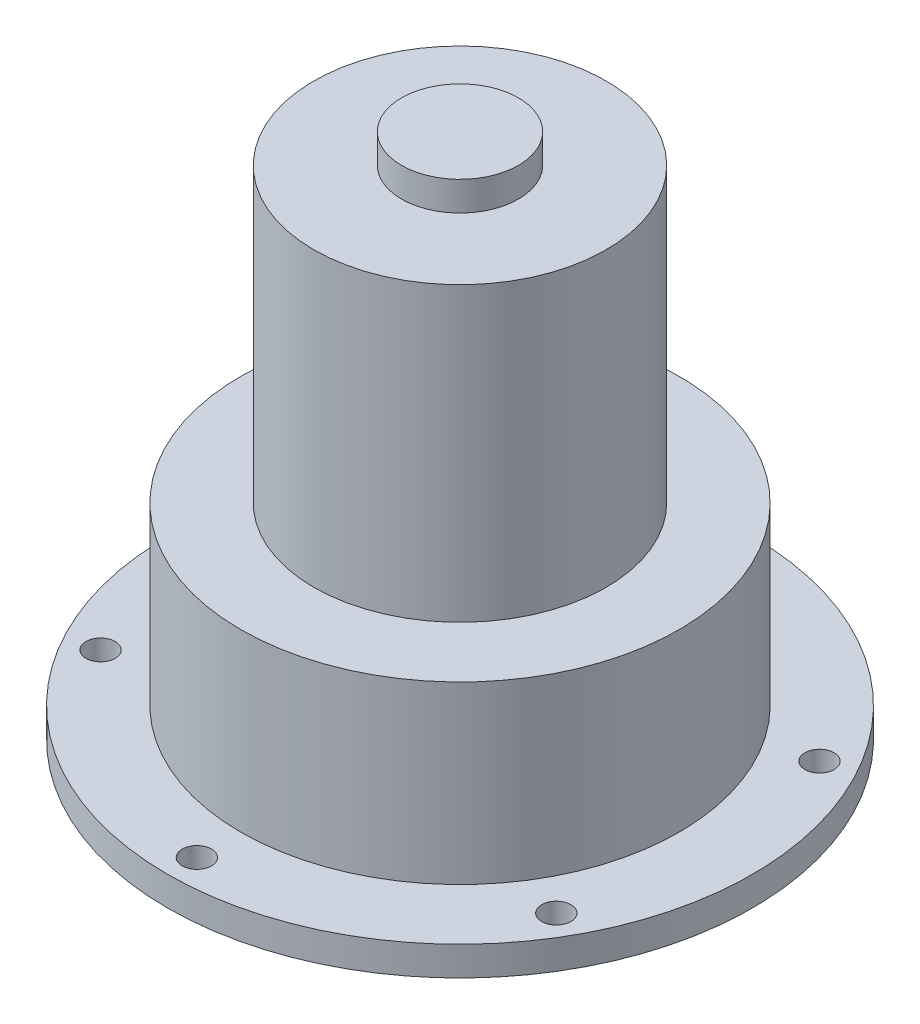
SolidWorks part; units mm, degrees
ref_plane "Front Plane" through (0, 0, 0) normal (0, 0, 1) x (1, 0, 0)
ref_plane "Top Plane" through (0, 0, 0) normal (0, 1, 0) x (1, 0, 0)
ref_plane "Right Plane" through (0, 0, 0) normal (1, 0, 0) x (0, 0, -1)
sketch "Sketch1" plane through (0, 0, 0) normal (0, 1, 0) x (1, 0, 0)
  circle A0 centre (0, 0) radius 37.5
  dimension "D1" = 75
extrude "Boss-Extrude1" add sketch "Sketch1" along normal blind 30
sketch "Sketch2" plane through (0, 30, 0) normal (0, 1, 0) x (1, 0, 0)
  circle A0 centre (0, 0) radius 25
  dimension "D1" = 50
extrude "Boss-Extrude2" add sketch "Sketch2" along normal blind 50
sketch "Sketch3" plane through (0, 80, 0) normal (0, 1, 0) x (1, 0, 0)
  circle A0 centre (0, 0) radius 10
  dimension "D1" = 20
extrude "Boss-Extrude3" add sketch "Sketch3" along normal blind 5
sketch "Sketch4" plane through (0, 0, 0) normal (0, -1, 0) x (1, 0, 0)
  circle A0 centre (0, 0) radius 50
  dimension "D1" = 100
extrude "Boss-Extrude4" add sketch "Sketch4" along normal blind 5
sketch "Sketch5" plane through (0, -5, 0) normal (0, -1, 0) x (1, 0, 0)
  circle A0 centre (0, 45) radius 2.5
  circle A1 centre (38.9711, 22.5) radius 2.5
  circle A2 centre (38.9711, -22.5) radius 2.5
  circle A3 centre (0, -45) radius 2.5
  circle A4 centre (-38.9711, -22.5) radius 2.5
  circle A5 centre (-38.9711, 22.5) radius 2.5
  point P15 (0, 0)
  dimension "D1" = 5
  dimension "D2" = 45
  dimension "D4" = 45
  dimension "D3" = 6
extrude "Cut-Extrude1" cut sketch "Sketch5" against normal blind 5
